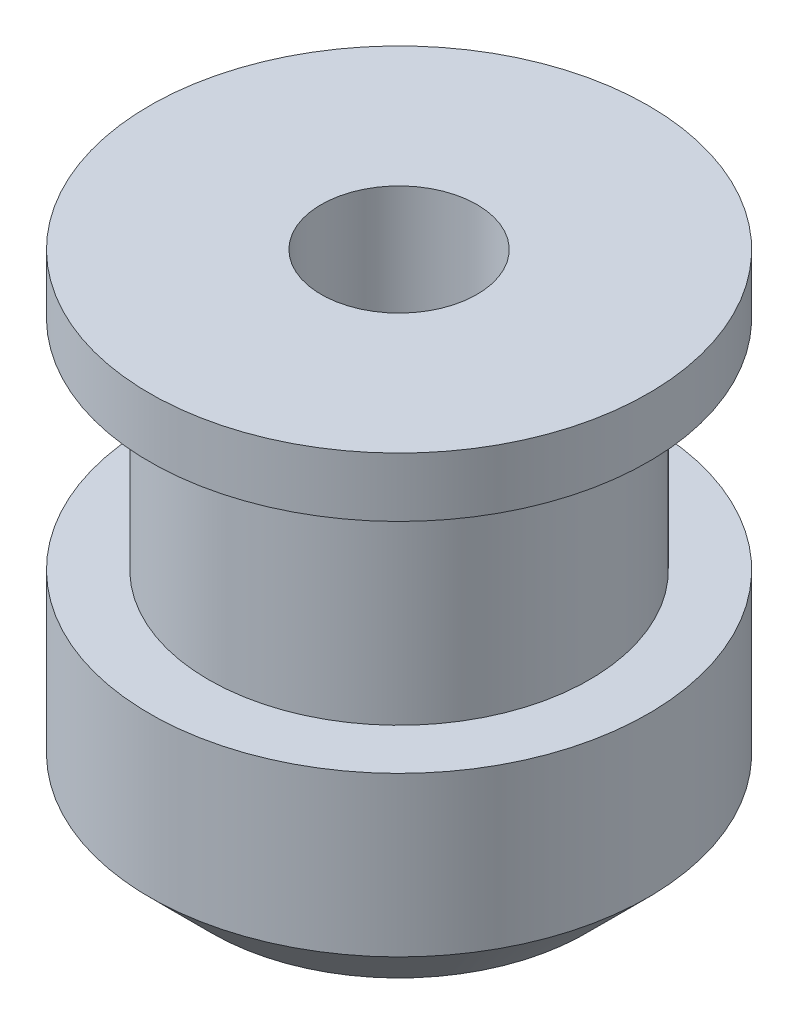
SolidWorks part; units mm, degrees
material "Plain Carbon Steel"
ref_plane "Front Plane" through (0, 0, 0) normal (0, 0, 1) x (1, 0, 0)
ref_plane "Top Plane" through (0, 0, 0) normal (0, 1, 0) x (1, 0, 0)
ref_plane "Right Plane" through (0, 0, 0) normal (1, 0, 0) x (0, 0, -1)
sketch "Sketch1" plane through (0, 0, 0) normal (0, 0, 1) x (1, 0, 0)
  line L0 (0, 0) -> (0, 16) construction
  line L1 (2.5, 0) -> (8, 0)
  line L2 (8, 0) -> (8, 7.1)
  line L3 (8, 7.1) -> (6.11, 7.1)
  line L4 (6.11, 7.1) -> (6.11, 14.1)
  line L5 (6.11, 14.1) -> (8, 14.1)
  line L6 (8, 14.1) -> (8, 16)
  line L7 (8, 16) -> (2.5, 16)
  line L8 (2.5, 16) -> (2.5, 0)
  dimension "D1" = 16
  dimension "D2" = 7.1
  dimension "D3" = 7
  dimension "D4" = 6.11
  dimension "D5" = 2.5
  dimension "D6" = 8
revolve "Revolve1" add sketch "Sketch1" angle 360 about L0
chamfer "Chamfer1" distance 2 angle 45 1 edges at (0, 0, -8)
